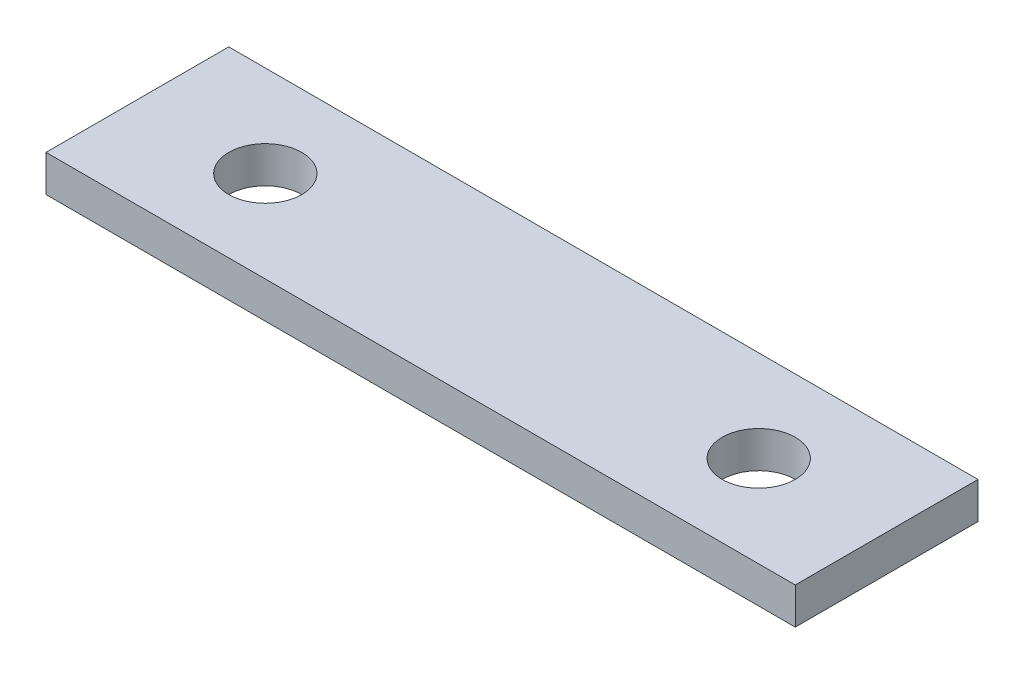
SolidWorks part; units mm, degrees
ref_plane "Front" through (0, 0, 0) normal (0, 0, 1) x (1, 0, 0)
ref_plane "Top" through (0, 0, 0) normal (0, 1, 0) x (1, 0, 0)
ref_plane "Right" through (0, 0, 0) normal (1, 0, 0) x (0, 0, -1)
sketch "Sketch1" plane through (0, 0, 0) normal (0, 1, 0) x (1, 0, 0)
  line L1 (0, 0) -> (35, 0)
  line L2 (0, 0) -> (0, 10)
  line L3 (0, 10) -> (35, 10)
  line L4 (35, 0) -> (35, 10)
  dimension "D1" = 35
  dimension "D2" = 10
extrude "Boss-Extrude1" add sketch "Sketch1" along normal blind 2
sketch "Sketch4" plane through (0, 0, 0) normal (0, -1, 0) x (1, 0, 0)
  line L0 (0, -10) -> (0, 0) construction
  line L1 (35, 0) -> (35, -10) construction
  line L2 (0, 0) -> (35, 0) construction
  line L5 (0, 0) -> (35, 0) construction
  circle A0 centre (4, -5) radius 2
  circle A1 centre (31, -5) radius 2
  dimension "D1" = 4
  dimension "D2" = 4
  dimension "D3" = 5
  dimension "D4" = 5
extrude "Cut-Extrude2" cut sketch "Sketch4" against normal blind 20
sketch "Sketch5" plane through (0, 0, 0) normal (-1, 0, 0) x (0, 0, 1)
  line L1 (0, 2) -> (-10, 2)
  line L2 (0, 2) -> (0, 0)
  line L3 (0, 0) -> (-10, 0)
  line L4 (-10, 2) -> (-10, 0)
extrude "Boss-Extrude3" add sketch "Sketch5" along normal blind 3
sketch "Sketch6" plane through (35, 0, 0) normal (1, 0, 0) x (0, 0, -1)
  line L1 (0, 0) -> (10, 0)
  line L2 (0, 0) -> (0, 2)
  line L3 (0, 2) -> (10, 2)
  line L4 (10, 0) -> (10, 2)
extrude "Boss-Extrude4" add sketch "Sketch6" along normal blind 3
